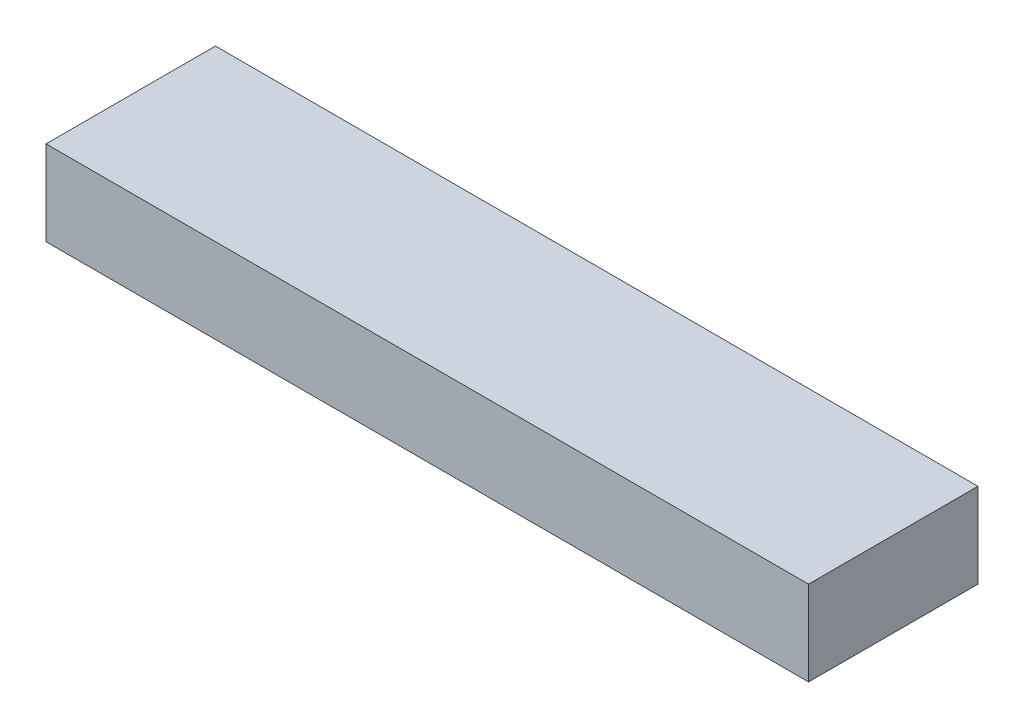
SolidWorks part; units mm, degrees
material "A-Glass Fiber"
ref_plane "Front Plane" through (0, 0, 0) normal (0, 0, 1) x (1, 0, 0)
ref_plane "Top Plane" through (0, 0, 0) normal (0, 1, 0) x (1, 0, 0)
ref_plane "Right Plane" through (0, 0, 0) normal (1, 0, 0) x (0, 0, -1)
sketch "Sketch2" plane through (0, 0, 0) normal (0, 1, 0) x (1, 0, 0)
  line L1 (-9, 16) -> (9, 16)
  line L2 (-9, 16) -> (-9, 12)
  line L3 (-9, 12) -> (9, 12)
  line L4 (9, 16) -> (9, 12)
  dimension "D1" = 4
  dimension "D2" = 18
extrude "Hirose Connector Stack" add sketch "Sketch2" along normal blind 2 contours L1 L4 L3 L2
